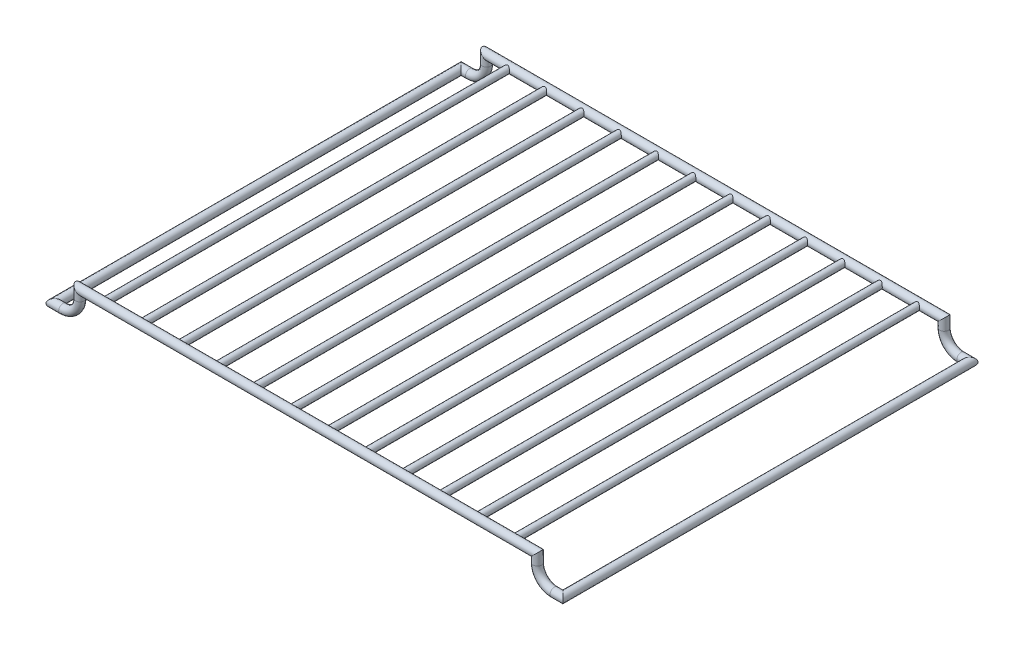
SolidWorks part; units mm, degrees
material "1023 Carbon Steel Sheet (SS)"
ref_plane "Front Plane" through (0, 0, 0) normal (0, 0, 1) x (1, 0, 0)
ref_plane "Top Plane" through (0, 0, 0) normal (0, 1, 0) x (1, 0, 0)
ref_plane "Right Plane" through (0, 0, 0) normal (1, 0, 0) x (0, 0, -1)
sketch3d "3DSketch1"
  line L0 (0, 0, 0) -> (135, 0, 0)
  line L1 (135, 0, 0) -> (135, -5, 0)
  line L2 (145, -15, 0) -> (150, -15, 0)
  line L3 (150, -15, 0) -> (150, -15, -240)
  line L4 (150, -15, -240) -> (145, -15, -240)
  line L5 (135, -5, -240) -> (135, 0, -240)
  line L6 (135, 0, -240) -> (0, 0, -240)
  arc A0 (135, -5, 0) -> (145, -15, 0) centre (145, -5, 0) ccw
  arc A1 (145, -15, -240) -> (135, -5, -240) centre (145, -5, -240) ccw
  point P11 (135, -15, 0)
  point P12 (145, -5, 10)
  point P15 (135, -15, -240)
  point P16 (145, -5, -250)
  dimension "D8" = 10
  dimension "D1" = 135
  dimension "D2" = 135
  dimension "D3" = 15
  dimension "D4" = 15
  dimension "D5" = 15
  dimension "D6" = 240
  dimension "D7" = 15
sketch "Sketch1" plane through (0, 0, 0) normal (1, 0, 0) x (0, 0, -1)
  circle A0 centre (0, 0) radius 2.5
  dimension "D1" = 5
sweep "Sweep1" add profiles "Sketch1" path "3DSketch1"
sketch "Sketch2" plane through (0, 0, 0) normal (0, 0, 1) x (1, 0, 0)
  circle A0 centre (11, 0) radius 2
  dimension "D2" = 4
  dimension "D1" = 11
extrude "Boss-Extrude1" add sketch "Sketch2" against normal up to surface (237.5 mm away)
pattern_linear "LPattern1" count 6 spacing 22 along (1, 0, 0) of "Boss-Extrude1"
mirror "Mirror1" about plane through (0, 0, -240) normal (-1, 0, 0) of bodies 103
